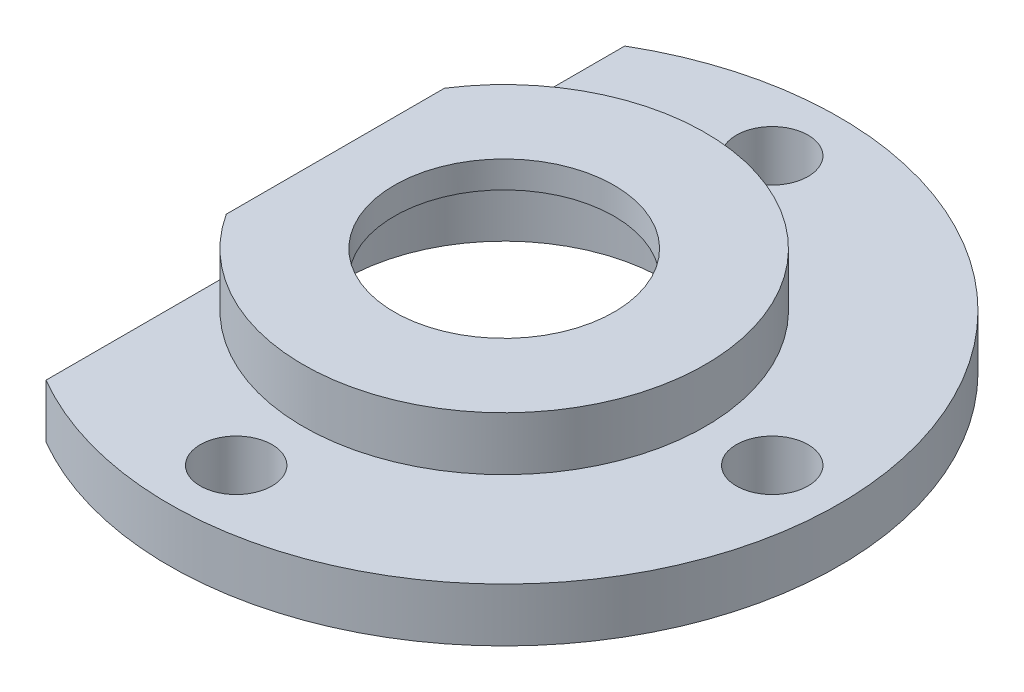
SolidWorks part; units mm, degrees
ref_plane "Front Plane" through (0, 0, 0) normal (0, 0, 1) x (1, 0, 0)
ref_plane "Top Plane" through (0, 0, 0) normal (0, 1, 0) x (1, 0, 0)
ref_plane "Right Plane" through (0, 0, 0) normal (1, 0, 0) x (0, 0, -1)
sketch "Sketch1" plane through (0, 0, 0) normal (0, 1, 0) x (1, 0, 0)
  circle A0 centre (0, 0) radius 15.875
  dimension "D1" = 31.75
extrude "Boss-Extrude1" add sketch "Sketch1" along normal blind 2.54
sketch "Sketch2" plane through (0, 2.54, 0) normal (0, 1, 0) x (1, 0, 0)
  circle A0 centre (0, 0) radius 9.525
  dimension "D1" = 19.05
extrude "Boss-Extrude2" add sketch "Sketch2" along normal blind 2.54
sketch "Sketch3" plane through (0, 0, 0) normal (0, -1, 0) x (1, 0, 0)
  circle A0 centre (0, 0) radius 7.62
  dimension "D1" = 15.24
extrude "Cut-Extrude1" cut sketch "Sketch3" against normal blind 3.81
sketch "Sketch4" plane through (0, 5.08, 0) normal (0, 1, 0) x (1, 0, 0)
  circle A0 centre (0, 0) radius 5.207
  dimension "D1" = 10.414
extrude "Cut-Extrude2" cut sketch "Sketch4" against normal up to next
sketch "Sketch5" plane through (0, 2.54, 0) normal (0, 1, 0) x (1, 0, 0)
  line L0 (0, 15.875) -> (0, 0) construction
  circle A0 centre (0, 12.7) radius 1.7
  circle A1 centre (0, 0) radius 15.875 construction
  circle A2 centre (12.7, 0) radius 1.7
  circle A3 centre (0, -12.7) radius 1.7
  circle A4 centre (-12.7, 0) radius 1.7
  point P18 (0, 0)
  dimension "D2" = 3.4
  dimension "D1" = 12.7
  dimension "D3" = 4
extrude "Cut-Extrude3" cut sketch "Sketch5" against normal up to next
sketch "Sketch6" plane through (0, 2.54, 0) normal (0, 1, 0) x (1, 0, 0)
  line L0 (-8, -13.7119) -> (-8, 13.7119)
  circle A1 centre (0, 0) radius 15.875 construction
  arc A2 (-8, -13.7119) -> (-8, 13.7119) centre (0, 0) cw
  circle M4 centre (-12.7, 0) radius 1.7
  circle M5 centre (0, 0) radius 9.525
  circle M6 centre (0, 0) radius 15.875
  dimension "D1" = 8
extrude "Cut-Extrude5" cut sketch "Sketch6" against normal up to next and the other way blind 2.794 contours L0 M5 | L0 M6 M5 M4
move or copy body "Body-Move/Copy1" bodies to move or copy 107 parameters "D1"=0, "D2"=0, "D3"=0
